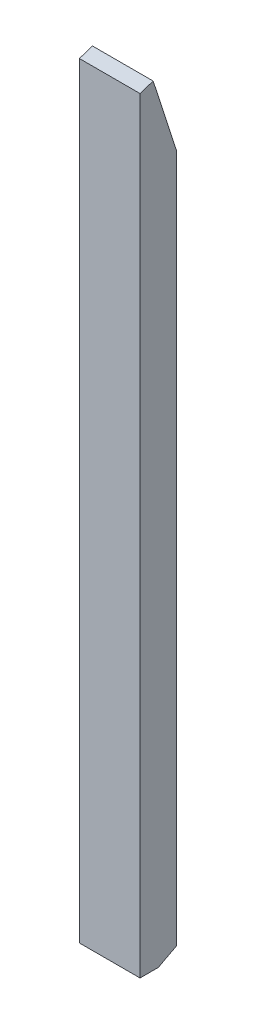
SolidWorks part; units mm, degrees
ref_plane "Front" through (0, 0, 0) normal (0, 0, 1) x (1, 0, 0)
ref_plane "Top" through (0, 0, 0) normal (0, 1, 0) x (1, 0, 0)
ref_plane "Right" through (0, 0, 0) normal (1, 0, 0) x (0, 0, -1)
sketch "Esquisse1" plane through (0, 0, 0) normal (0, 0, 1) x (1, 0, 0)
  line L1 (0, 0) -> (63, 0)
  line L2 (0, 0) -> (0, 800)
  line L3 (0, 800) -> (63, 800)
  line L4 (63, 0) -> (63, 800)
  dimension "D1" = 63
  dimension "D2" = 800
extrude "Boss.-Extru.1" add sketch "Esquisse1" along normal blind 38
sketch "Esquisse2" plane through (0, 0, 0) normal (-1, 0, 0) x (0, 0, 1)
  line L0 (24.369, 800) -> (0, 725)
  line L1 (38, 800) -> (0, 800) construction
  line L2 (0, 800) -> (0, 0) construction
  line L3 (0, 725) -> (0, 800)
  line L4 (0, 800) -> (24.369, 800)
  line L5 (19, 0) -> (0, 10)
  line L6 (38, 0) -> (0, 0) construction
  line L7 (0, 10) -> (0, 0)
  line L8 (0, 0) -> (19, 0)
  dimension "D1" = 18
  dimension "D2" = 75
  dimension "D3" = 10
extrude "Enlèv. mat.-Extru.1" cut sketch "Esquisse2" against normal through all
sketch "Esquisse3" plane through (0, 0, 0) normal (-1, 0, 0) x (0, 0, 1)
  line L0 (24.369, 800) -> (38, 795.571)
  line L1 (38, 800) -> (24.369, 800) construction
  line L2 (38, 800) -> (38, 0) construction
  line L3 (38, 795.571) -> (38, 800)
  line L4 (38, 800) -> (24.369, 800)
  line L5 (0, 725) -> (24.369, 800) construction
  point P6 (24.369, 800)
  dimension "D1" = 18
extrude "Enlèv. mat.-Extru.2" cut sketch "Esquisse3" against normal through all
